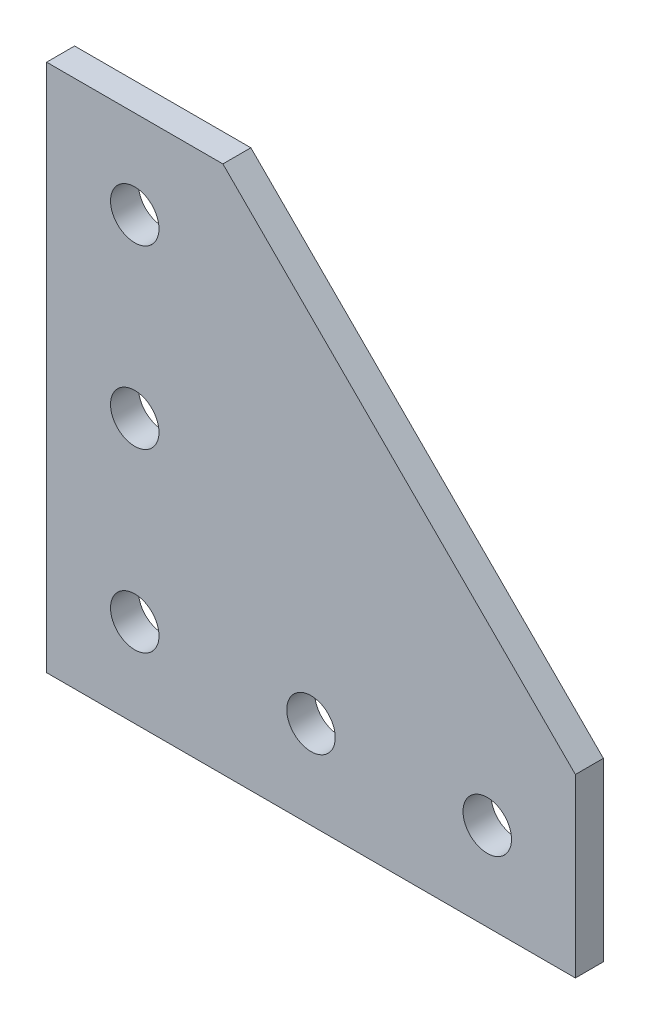
SolidWorks part; units mm, degrees
ref_plane "Front Plane" through (0, 0, 0) normal (0, 0, 1) x (1, 0, 0)
ref_plane "Top Plane" through (0, 0, 0) normal (0, 1, 0) x (1, 0, 0)
ref_plane "Right Plane" through (0, 0, 0) normal (1, 0, 0) x (0, 0, -1)
sketch "Sketch1" plane through (0, 0, 0) normal (0, 0, 1) x (1, 0, 0)
  line L0 (0, 0) -> (0, 60)
  line L1 (0, 60) -> (20, 60)
  line L2 (20, 60) -> (60, 20)
  line L3 (60, 20) -> (60, 0)
  line L4 (60, 0) -> (0, 0)
  dimension "D1" = 20
  dimension "D2" = 60
extrude "Boss-Extrude1" add sketch "Sketch1" along normal blind 3.175
hole_wizard "M5 Clearance Hole1" positions "3DSketch1" profile "Sketch2" hole size "M5" standard "ANSI Metric" end condition through all
sketch3d "3DSketch1"
  line L0 (0, 60, 3.175) -> (0, 0, 3.175) construction
  line L1 (0, 0, 3.175) -> (60, 0, 3.175) construction
  point P4 (10, 10, 3.175)
  dimension "D1" = 10
  dimension "D2" = 10
sketch "Sketch2" plane through (10, 10, 3.175) normal (1, 0, 0) x (0, -1, 0)
  line L0 (0, 0) -> (0, 3.175)
  line L1 (0, 3.175) -> (2.75, 3.175)
  line L2 (2.75, 3.175) -> (2.75, 0)
  line L5 (2.75, 0) -> (0, 0)
  line L11 (0, -6.35) -> (0, 107.95) construction
  dimension "Thru Hole Dia." = 5.5
  dimension "Thru Hole Depth" = 3.175
pattern_linear "LPattern1" count 3 spacing 20 along (1, 0, 0) of "M5 Clearance Hole1"
pattern_linear "LPattern2" count 3 spacing 20 along (0, 1, 0) of "M5 Clearance Hole1"
